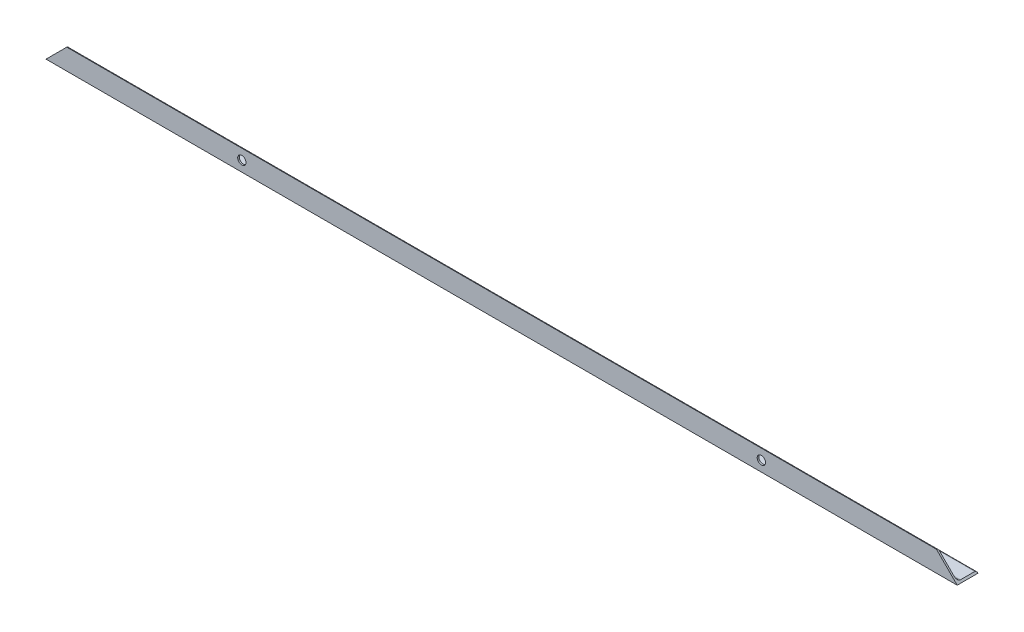
SolidWorks part; units mm, degrees
ref_plane "Front Plane" through (0, 0, 0) normal (0, 0, 1) x (1, 0, 0)
ref_plane "Top Plane" through (0, 0, 0) normal (0, 1, 0) x (1, 0, 0)
ref_plane "Right Plane" through (0, 0, 0) normal (1, 0, 0) x (0, 0, -1)
sketch "Sketch1" plane through (0, 0, 0) normal (0, 1, 0) x (1, 0, 0)
  line L0 (0, 0) -> (1754, 0)
  dimension "D1" = 1754
other "L angle (equal) 40X40X3(6)"
ref_plane "Plane1" through (0, 0, 0) normal (1, 0, 0) x (0, 0, -1)
sketch "Sketch13" plane through (0, 0, 0) normal (1, 0, 0) x (0, 0, -1)
  line L0 (0, 40) -> (0, 0)
  line L2 (3, 37) -> (3, 9)
  line L3 (9, 3) -> (37, 3)
  line L5 (40, 0) -> (0, 0)
  arc A0 (3, 37) -> (0, 40) centre (0, 37) ccw
  arc A1 (40, 0) -> (37, 3) centre (37, 0) ccw
  arc A2 (9, 3) -> (3, 9) centre (9, 9) cw
  point P8 (0, 20)
  point P9 (20, 0)
  point P10 (0, 0)
  dimension "Radius_2" = 3
  dimension "Radius_1" = 6
  dimension "V_leg" = 40
  dimension "H_leg" = 40
  dimension "thickness" = 3
sketch "Sketch14" plane through (0, 0, 0) normal (0, 0, 1) x (1, 0, 0)
  line L0 (1754, 0) -> (1754, 40)
  line L1 (0, 40) -> (0, 0)
  line L2 (40, 40) -> (0, 0)
  line L3 (1714, 40) -> (1754, 0)
  line L4 (0, 40) -> (0, 0)
  line L5 (0, 0) -> (1754, 0)
  line L6 (1754, 0) -> (1754, 40)
  line L7 (1754, 40) -> (0, 40)
  line L8 (0, 40) -> (0, 0) construction
  line L10 (1754, 0) -> (1754, 40) construction
  line L11 (1754, 40) -> (1714, 40)
  line L12 (40, 40) -> (0, 40)
  line L13 (40, 40) -> (1714, 40) construction
  line L14 (877, 40) -> (877, 0) construction
  line L15 (1754, 0) -> (0, 0) construction
  line L16 (377, 40) -> (377, 0) construction
  line L17 (1377, 40) -> (1377, 0) construction
  circle A1 centre (377, 20) radius 8
  circle A2 centre (1377, 20) radius 8
  dimension "D3" = 500
  dimension "D5" = 877
  dimension "D2" = 40
  dimension "D6" = 877
  dimension "D1" = 0
  dimension "D4" = 500
extrude "Cut-Extrude1" cut sketch "Sketch14" against normal through all
